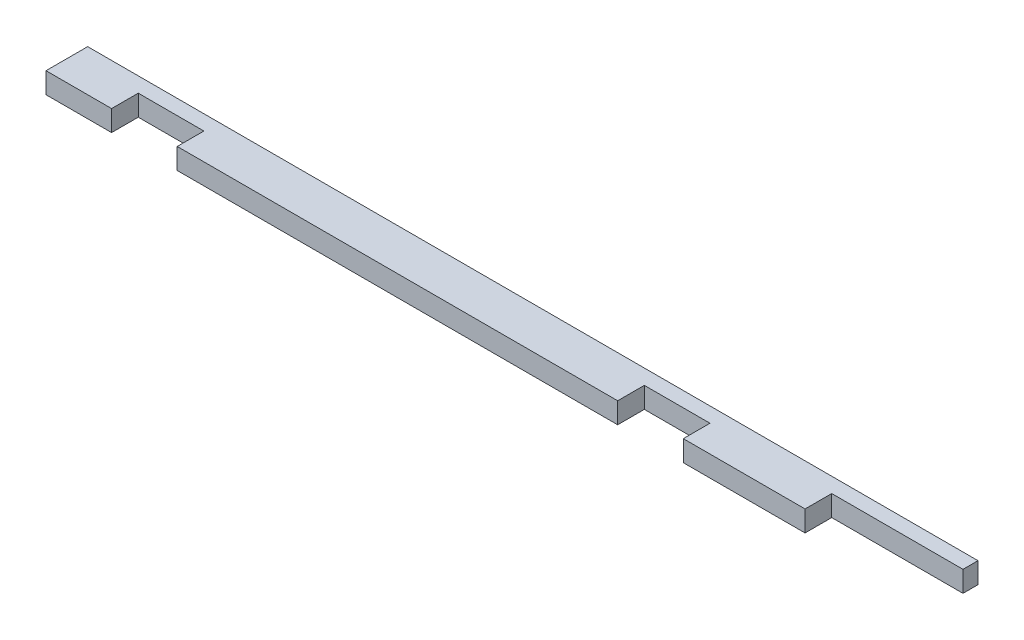
SolidWorks part; units mm, degrees
ref_plane "Front Plane" through (0, 0, 0) normal (0, 0, 1) x (1, 0, 0)
ref_plane "Top Plane" through (0, 0, 0) normal (0, 1, 0) x (1, 0, 0)
ref_plane "Right Plane" through (0, 0, 0) normal (1, 0, 0) x (0, 0, -1)
sketch "Sketch1" plane through (0, 0, 0) normal (0, 1, 0) x (1, 0, 0)
  line L0 (0, 0) -> (4.9964, 0)
  line L1 (0, 3.175) -> (67.8269, 3.175)
  line L2 (9.9951, 2.032) -> (9.9951, 0)
  line L3 (0, 2.032) -> (67.8269, 2.032) construction
  line L4 (0, 3.175) -> (0, 0)
  line L5 (57.8269, 2.032) -> (67.8269, 2.032)
  line L6 (57.8269, 2.032) -> (57.8269, 0)
  line L8 (48.5513, 2.032) -> (48.5513, 0)
  line L9 (29.2756, 0) -> (43.5513, 0)
  line L10 (43.5513, 0) -> (43.5513, 2.032)
  line L11 (19.2756, 0) -> (29.2756, 0)
  line L12 (67.8269, 2.032) -> (67.8269, 3.175)
  line L13 (48.5513, 0) -> (57.8269, 0)
  line L14 (43.5513, 2.032) -> (48.5513, 2.032)
  line L15 (19.2756, 0) -> (9.9951, 0)
  line L19 (4.9964, 0) -> (4.9964, 2.032)
  line L20 (4.9964, 2.032) -> (9.9951, 2.032)
  dimension "D1" = 10
  dimension "D2" = 4.9987
  dimension "D3" = 4.9964
  dimension "D4" = 1.143
  dimension "D5" = 5
  dimension "D6" = 14.2756
  dimension "D7" = 2.032
  dimension "D8" = 9.2756
  dimension "D9" = 10
  dimension "D11" = 67.8269
extrude "Boss-Extrude1" add sketch "Sketch1" along normal blind 1.5875
